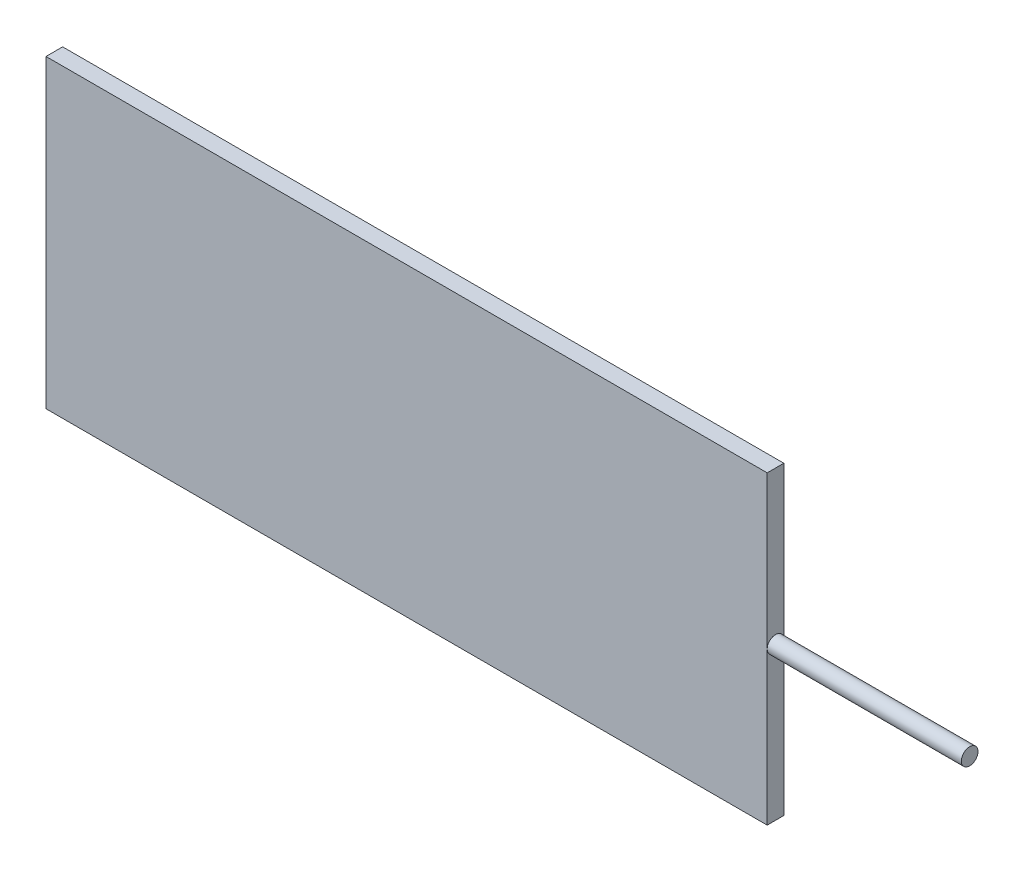
SolidWorks part; units mm, degrees
ref_plane "前视基准面" through (0, 0, 0) normal (0, 0, 1) x (1, 0, 0)
ref_plane "上视基准面" through (0, 0, 0) normal (0, 1, 0) x (1, 0, 0)
ref_plane "右视基准面" through (0, 0, 0) normal (1, 0, 0) x (0, 0, -1)
sketch "草图1" plane through (0, 0, 0) normal (0, 0, 1) x (1, 0, 0)
  line L1 (0, 0) -> (260, 0)
  line L2 (0, 0) -> (0, 110)
  line L3 (0, 110) -> (260, 110)
  line L4 (260, 0) -> (260, 110)
  dimension "D1" = 110
  dimension "D2" = 260
extrude "凸台-拉伸1" add sketch "草图1" along normal blind 6
sketch "草图2" plane through (260, 0, 0) normal (1, 0, 0) x (0, 0, -1)
  line L0 (-6, 55) -> (0, 55) construction
  line L1 (-6, 0) -> (-6, 110) construction
  line L2 (0, 0) -> (0, 110) construction
  circle A0 centre (-3, 55) radius 3
extrude "凸台-拉伸2" add sketch "草图2" along normal blind 70
